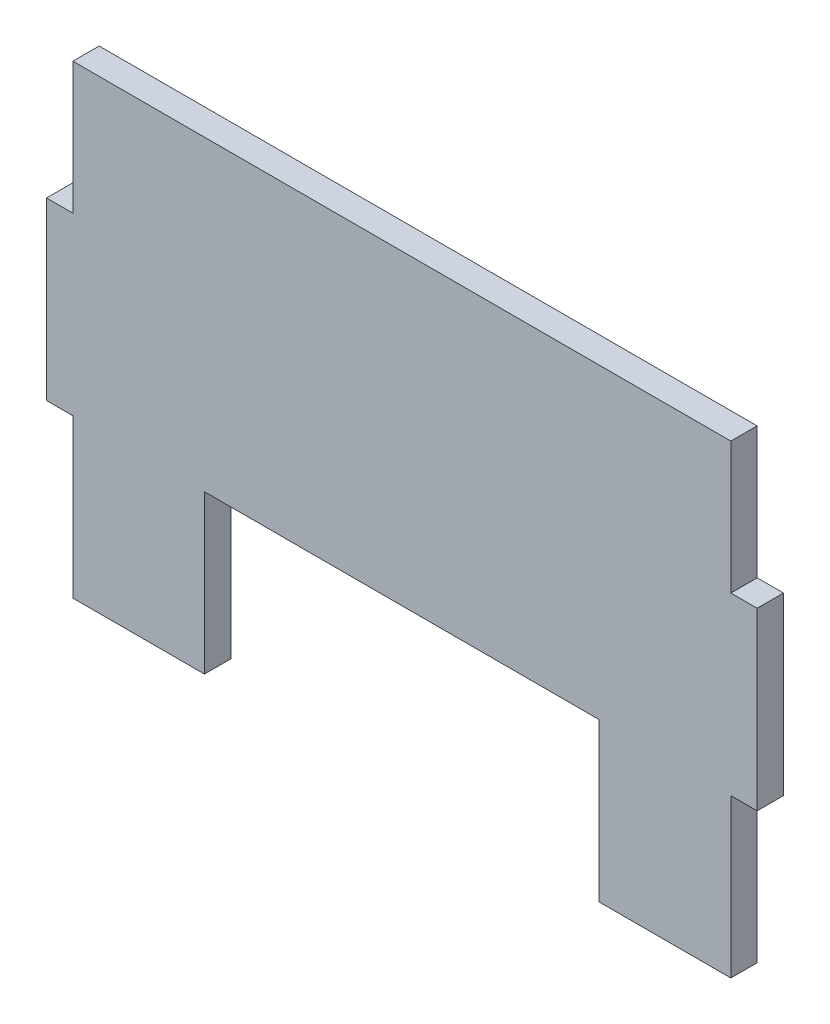
SolidWorks part; units mm, degrees
ref_plane "Plano frontal" through (0, 0, 0) normal (0, 0, 1) x (1, 0, 0)
ref_plane "Plano superior" through (0, 0, 0) normal (0, 1, 0) x (1, 0, 0)
ref_plane "Plano direito" through (0, 0, 0) normal (1, 0, 0) x (0, 0, -1)
sketch "Esboço1" plane through (0, 0, 0) normal (0, 0, 1) x (1, 0, 0)
  line L1 (75, -50) -> (-75, -50)
  line L2 (75, -50) -> (75, 50)
  line L3 (75, 50) -> (-75, 50)
  line L4 (-75, -50) -> (-75, 50)
  line L5 (75, -50) -> (-75, 50) construction
  line L6 (75, 50) -> (-75, -50) construction
  point P0 (0, 0)
  dimension "D1" = 150
  dimension "D2" = 100
extrude "Ressalto-extrusão2" add sketch "Esboço1" along normal blind 6
sketch "Esboço3" plane through (0, 0, 6) normal (0, 0, 1) x (1, 0, 0)
  line L0 (-75, -50) -> (75, -50) construction
  line L1 (-45, -50) -> (45, -50)
  line L2 (-45, -50) -> (-45, -20)
  line L3 (-45, -20) -> (45, -20)
  line L4 (45, -50) -> (45, -20)
  line L5 (-75, 50) -> (-75, -50) construction
  line L6 (75, -50) -> (75, 50) construction
  dimension "D1" = 30
  dimension "30" = 30
  dimension "D3" = 30
extrude "Corte-extrusão1" cut sketch "Esboço3" against normal through all contours L2 L1 L4 L3
sketch "Esboço4" plane through (75, 0, 0) normal (1, 0, 0) x (0, 0, -1)
  line L0 (0, -50) -> (0, 50) construction
  line L1 (0, 20) -> (-6, 20)
  line L2 (0, 20) -> (0, -20)
  line L3 (0, -20) -> (-6, -20)
  line L4 (-6, 20) -> (-6, -20)
  line L5 (-6, -50) -> (-6, 50) construction
  dimension "D1" = 40
  dimension "D2" = 30
extrude "Ressalto-extrusão4" add sketch "Esboço4" along normal blind 6
sketch "Esboço5" plane through (-75, 0, 0) normal (-1, 0, 0) x (0, 0, 1)
  line L0 (0, 50) -> (0, -50) construction
  line L1 (0, 20) -> (6, 20)
  line L2 (0, 20) -> (0, -20)
  line L3 (0, -20) -> (6, -20)
  line L4 (6, 20) -> (6, -20)
  line L5 (6, 50) -> (6, -50) construction
  dimension "D1" = 40
  dimension "D2" = 30
extrude "Ressalto-extrusão5" add sketch "Esboço5" along normal blind 6
sketch "Esboço7" plane through (0, -50, 0) normal (0, -1, 0) x (1, 0, 0)
  line L1 (75, 6) -> (45, 6)
  line L2 (75, 6) -> (75, 0)
  line L3 (75, 0) -> (45, 0)
  line L4 (45, 6) -> (45, 0)
extrude "Ressalto-extrusão7" add sketch "Esboço7" along normal blind 6
sketch "Esboço8" plane through (0, -50, 0) normal (0, -1, 0) x (1, 0, 0)
  line L1 (-45, 6) -> (-75, 6)
  line L2 (-45, 6) -> (-45, 0)
  line L3 (-45, 0) -> (-75, 0)
  line L4 (-75, 6) -> (-75, 0)
extrude "Ressalto-extrusão8" add sketch "Esboço8" along normal blind 6
